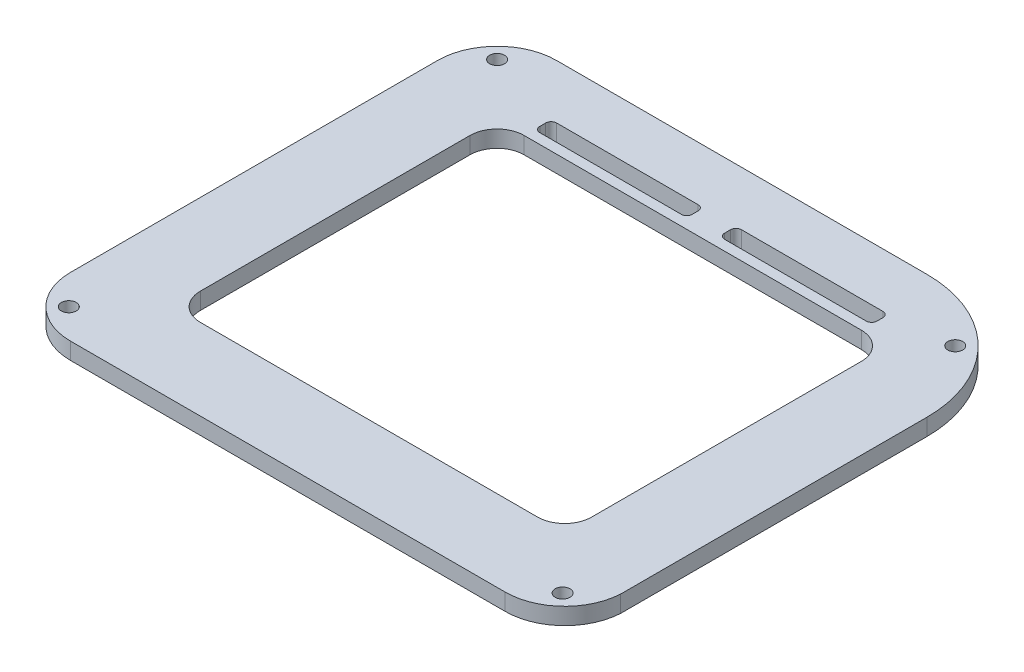
SolidWorks part; units mm, degrees
material "PMMA"
ref_plane "Front Plane" through (0, 0, 0) normal (0, 0, 1) x (1, 0, 0)
ref_plane "Top Plane" through (0, 0, 0) normal (0, 1, 0) x (1, 0, 0)
ref_plane "Right Plane" through (0, 0, 0) normal (1, 0, 0) x (0, 0, -1)
sketch "Sketch1" plane through (0, 0, 0) normal (0, 1, 0) x (1, 0, 0)
  line L0 (-39.7107, 45.6014) -> (28.7393, 45.6014)
  line L1 (51.6193, 22.7214) -> (51.6193, -33.9106)
  line L2 (-39.7107, -44.2386) -> (40.6398, -44.2386)
  line L3 (-50.7107, 34.6014) -> (-50.7107, -33.2386)
  line L8 (-43.2463, 38.1369) -> (-47.4889, 42.3796) construction
  line L9 (-43.2463, -36.7741) -> (-47.4889, -41.0168) construction
  line L10 (44.0115, -36.9308) -> (48.1767, -41.2508) construction
  line L11 (40.6752, 34.6574) -> (44.9179, 38.9) construction
  line L12 (36.6193, -24.2386) -> (36.6193, 25.6014)
  line L13 (31.6193, 30.6014) -> (-30.7107, 30.6014)
  line L14 (-35.7107, 25.6014) -> (-35.7107, -24.2386)
  line L15 (-30.7107, -29.2386) -> (31.6193, -29.2386)
  line L16 (4.4543, 35.6014) -> (30.6193, 35.6014)
  line L17 (-29.7107, 35.6014) -> (-3.5457, 35.6014)
  line L18 (-30.7107, 34.6014) -> (-30.7107, 33.5014)
  line L19 (-29.7107, 32.5014) -> (-3.5457, 32.5014)
  line L20 (31.6193, 34.6014) -> (31.6193, 33.5014)
  line L21 (-2.5457, 34.6014) -> (-2.5457, 33.5014)
  line L22 (3.4543, 34.6014) -> (3.4543, 33.5014)
  line L23 (4.4543, 32.5014) -> (30.6193, 32.5014)
  arc A0 (51.6193, 22.7214) -> (28.7393, 45.6014) centre (28.7393, 22.7214) ccw
  arc A1 (51.6193, -33.9106) -> (40.6398, -44.2386) centre (40.6398, -33.2386) cw
  arc A2 (-50.7107, -33.2386) -> (-39.7107, -44.2386) centre (-39.7107, -33.2386) ccw
  arc A3 (-39.7107, 45.6014) -> (-50.7107, 34.6014) centre (-39.7107, 34.6014) ccw
  circle A8 centre (-45.3676, 40.2582) radius 1.375
  circle A9 centre (-45.3676, -38.8955) radius 1.375
  circle A10 centre (46.0941, -39.0908) radius 1.375
  circle A11 centre (42.7965, 36.7787) radius 1.375
  arc A12 (-35.7107, 25.6014) -> (-30.7107, 30.6014) centre (-30.7107, 25.6014) cw
  arc A13 (-35.7107, -24.2386) -> (-30.7107, -29.2386) centre (-30.7107, -24.2386) ccw
  arc A14 (31.6193, 30.6014) -> (36.6193, 25.6014) centre (31.6193, 25.6014) cw
  arc A15 (36.6193, -24.2386) -> (31.6193, -29.2386) centre (31.6193, -24.2386) cw
  arc A16 (31.6193, 34.6014) -> (30.6193, 35.6014) centre (30.6193, 34.6014) ccw
  arc A17 (31.6193, 33.5014) -> (30.6193, 32.5014) centre (30.6193, 33.5014) cw
  arc A18 (-30.7107, 34.6014) -> (-29.7107, 35.6014) centre (-29.7107, 34.6014) cw
  arc A19 (-30.7107, 33.5014) -> (-29.7107, 32.5014) centre (-29.7107, 33.5014) ccw
  arc A20 (-2.5457, 34.6014) -> (-3.5457, 35.6014) centre (-3.5457, 34.6014) ccw
  arc A21 (-2.5457, 33.5014) -> (-3.5457, 32.5014) centre (-3.5457, 33.5014) cw
  arc A22 (3.4543, 33.5014) -> (4.4543, 32.5014) centre (4.4543, 33.5014) ccw
  arc A23 (3.4543, 34.6014) -> (4.4543, 35.6014) centre (4.4543, 34.6014) cw
  dimension "D4" = 2.75
  dimension "D3" = 5
  dimension "D5" = 5
  dimension "D6" = 5
  dimension "D11" = 1
  dimension "D12" = 1
  dimension "D13" = 1
  dimension "D14" = 1
  dimension "D15" = 1
  dimension "D16" = 1
  dimension "D17" = 1
  dimension "D18" = 1
  dimension "D1" = 89.84
  dimension "D2" = 102.33
  dimension "D7" = 3.1
  dimension "D8" = 5
  dimension "D9" = 5
  dimension "D10" = 5
extrude "Boss-Extrude1" add sketch "Sketch1" along normal blind 3.1
